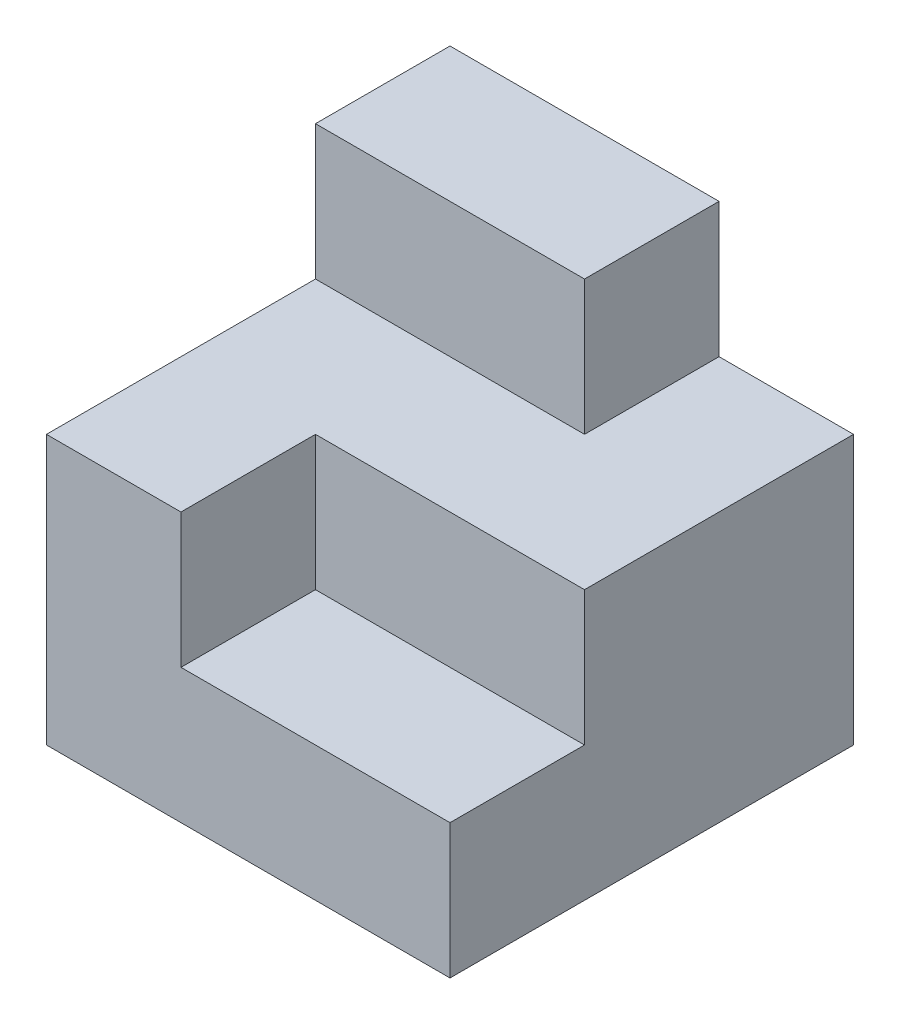
SolidWorks part; units mm, degrees
ref_plane "Alzado" through (0, 0, 0) normal (0, 0, 1) x (1, 0, 0)
ref_plane "Planta" through (0, 0, 0) normal (0, 1, 0) x (1, 0, 0)
ref_plane "Vista lateral" through (0, 0, 0) normal (1, 0, 0) x (0, 0, -1)
sketch "Croquis1" plane through (0, 0, 0) normal (0, 1, 0) x (1, 0, 0)
  line L1 (-116.7861, 29.9772) -> (-86.7861, 29.9772)
  line L2 (-116.7861, 29.9772) -> (-116.7861, -0.0228)
  line L3 (-116.7861, -0.0228) -> (-86.7861, -0.0228)
  line L4 (-86.7861, 29.9772) -> (-86.7861, -0.0228)
  line L5 (-116.7861, 29.9772) -> (-86.7861, -0.0228) construction
  line L6 (-116.7861, -0.0228) -> (-86.7861, 29.9772) construction
  point P4 (-101.7861, 14.9772)
  dimension "D1" = 30
  dimension "D2" = 30
extrude "Saliente-Extruir1" add sketch "Croquis1" along normal blind 10
sketch "Croquis3" plane through (0, 10, 0) normal (0, 1, 0) x (1, 0, 0)
  line L0 (-116.7861, -0.0228) -> (-86.7861, -0.0228) construction
  line L1 (-116.7861, 29.9772) -> (-106.7861, 29.9772)
  line L2 (-116.7861, 29.9772) -> (-116.7861, -0.0228)
  line L3 (-116.7861, -0.0228) -> (-106.7861, -0.0228)
  line L4 (-106.7861, 9.9772) -> (-106.7861, -0.0228)
  line L7 (-106.7861, 29.9772) -> (-86.7861, 29.9772)
  line L8 (-86.7861, 29.9772) -> (-86.7861, 9.9772)
  line L9 (-86.7861, 9.9772) -> (-106.7861, 9.9772)
  point P4 (-111.7861, 14.9772)
  dimension "D1" = 10
  dimension "D2" = 30
  dimension "D3" = 20
extrude "Saliente-Extruir2" add sketch "Croquis3" along normal blind 10
sketch "Croquis5" plane through (0, 20, 0) normal (0, 1, 0) x (1, 0, 0)
  line L1 (-116.7861, 29.9772) -> (-96.7861, 29.9772)
  line L2 (-116.7861, 29.9772) -> (-116.7861, 19.9772)
  line L3 (-116.7861, 19.9772) -> (-96.7861, 19.9772)
  line L4 (-96.7861, 29.9772) -> (-96.7861, 19.9772)
  line L5 (-116.7861, 29.9772) -> (-96.7861, 19.9772) construction
  line L6 (-116.7861, 19.9772) -> (-96.7861, 29.9772) construction
  point P4 (-106.7861, 24.9772)
extrude "Saliente-Extruir3" add sketch "Croquis5" along normal blind 10
